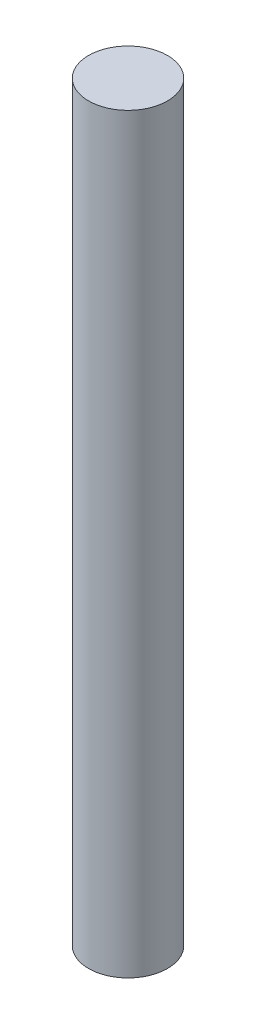
SolidWorks part; units mm, degrees
ref_plane "Front Plane" through (0, 0, 0) normal (0, 0, 1) x (1, 0, 0)
ref_plane "Top Plane" through (0, 0, 0) normal (0, 1, 0) x (1, 0, 0)
ref_plane "Right Plane" through (0, 0, 0) normal (1, 0, 0) x (0, 0, -1)
sketch "Sketch1" plane through (0, 0, 0) normal (0, 1, 0) x (1, 0, 0)
  circle A0 centre (0, 0) radius 4
  dimension "D1" = 8
extrude "Boss-Extrude1" add sketch "Sketch1" along normal blind 76.2 contours A0
